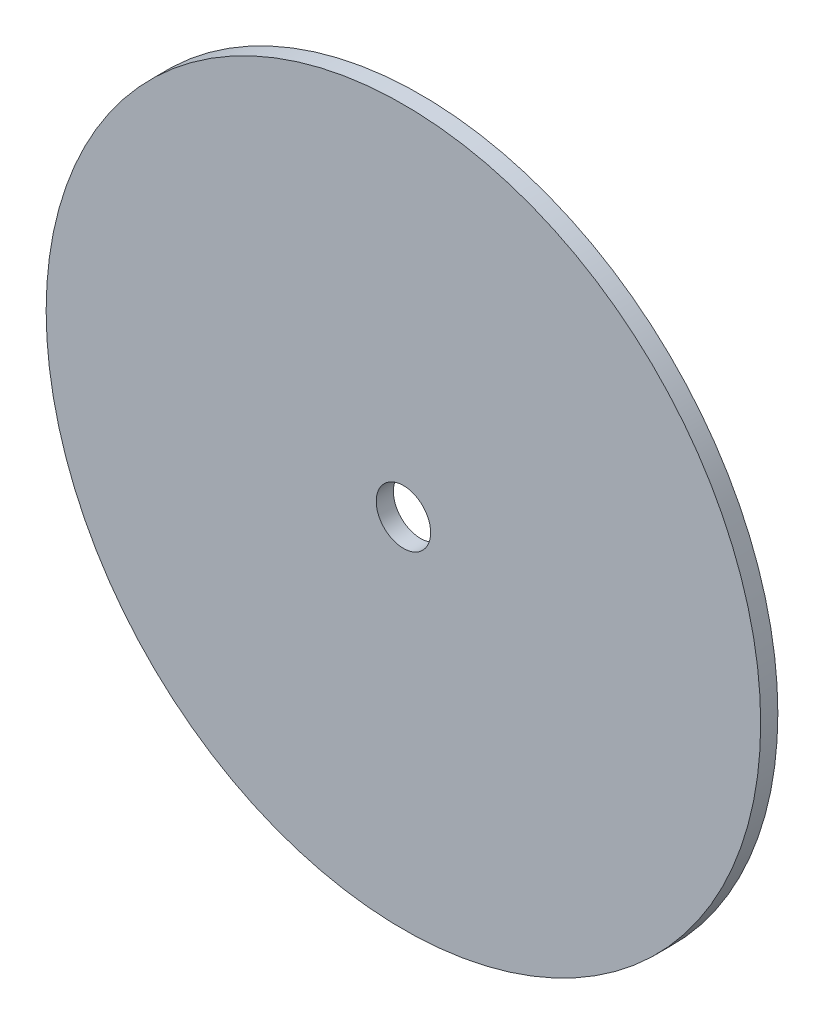
SolidWorks part; units mm, degrees
material "Pine"
ref_plane "Front Plane" through (0, 0, 0) normal (0, 0, 1) x (1, 0, 0)
ref_plane "Top Plane" through (0, 0, 0) normal (0, 1, 0) x (1, 0, 0)
ref_plane "Right Plane" through (0, 0, 0) normal (1, 0, 0) x (0, 0, -1)
sketch "Sketch1" plane through (0, 0, 0) normal (1, 0, 0) x (0, 0, -1)
  line L0 (0, 0) -> (33.6585, 0) construction
  line L1 (0, 125) -> (6, 125)
  line L2 (6, 125) -> (6, 9.525)
  line L3 (6, 9.525) -> (0, 9.525)
  line L4 (0, 9.525) -> (0, 125)
  dimension "D1" = 6
  dimension "D2" = 250
  dimension "D3" = 19.05
revolve "Revolve1" add sketch "Sketch1" angle 360 about L0
